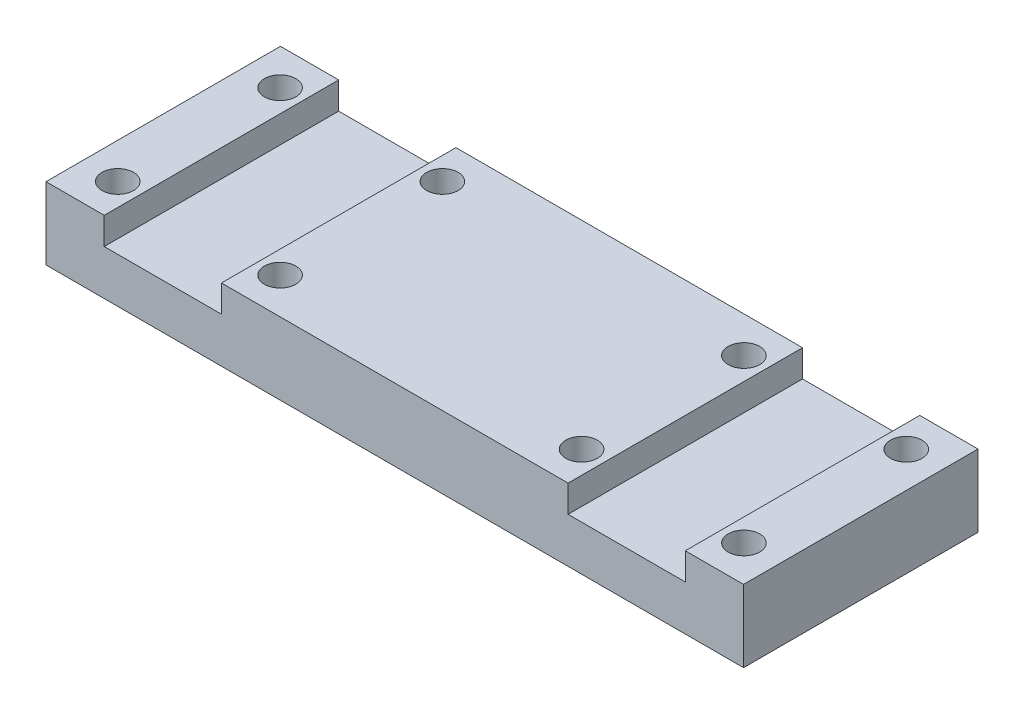
SolidWorks part; units mm, degrees
ref_plane "Front Plane" through (0, 0, 0) normal (0, 0, 1) x (1, 0, 0)
ref_plane "Top Plane" through (0, 0, 0) normal (0, 1, 0) x (1, 0, 0)
ref_plane "Right Plane" through (0, 0, 0) normal (1, 0, 0) x (0, 0, -1)
sketch "Sketch1" plane through (0, 0, 0) normal (0, 1, 0) x (1, 0, 0)
  line L1 (-77.35, -26) -> (77.35, -26)
  line L2 (-77.35, -26) -> (-77.35, 26)
  line L3 (-77.35, 26) -> (77.35, 26)
  line L4 (77.35, -26) -> (77.35, 26)
  line L5 (-77.35, -26) -> (77.35, 26) construction
  line L6 (-77.35, 26) -> (77.35, -26) construction
  point P0 (0, 0)
  dimension "D1" = 52
  dimension "D2" = 154.7
extrude "Boss-Extrude1" add sketch "Sketch1" along normal blind 16
sketch "Sketch2" plane through (77.35, 0, 0) normal (1, 0, 0) x (0, 0, -1)
  line L0 (-26, 16) -> (26, 16) construction
  line L1 (-13, 16) -> (13, 16)
  line L2 (-13, 16) -> (-13, 10)
  line L3 (-13, 10) -> (13, 10)
  line L4 (13, 16) -> (13, 10)
  point P6 (0, 16)
  point P7 (0, 16)
  dimension "D1" = 26
  dimension "D2" = 6
extrude "Cut-Extrude1" [suppressed] cut sketch "Sketch2" against normal through all
sketch "Sketch3" plane through (0, 16, 0) normal (0, 1, 0) x (1, 0, 0)
  line L0 (-77.35, 26) -> (-77.35, -26) construction
  line L1 (-33.4356, -18) -> (-69.4356, -18) construction
  line L2 (-33.4356, -18) -> (-33.4356, 18) construction
  line L3 (-33.4356, 18) -> (-69.4356, 18) construction
  line L4 (-69.4356, -18) -> (-69.4356, 18) construction
  line L5 (-33.4356, -18) -> (-69.4356, 18) construction
  line L6 (-33.4356, 18) -> (-69.4356, -18) construction
  line L9 (-75.85, 18) -> (-72.6428, 12.445) construction
  line L10 (-72.6428, 12.445) -> (-66.2285, 12.445) construction
  line L11 (-66.2285, 12.445) -> (-63.0213, 18) construction
  line L12 (-63.0213, 18) -> (-66.2285, 23.555) construction
  line L13 (-66.2285, 23.555) -> (-72.6428, 23.555) construction
  line L14 (-72.6428, 23.555) -> (-75.85, 18) construction
  circle A0 centre (-69.4356, 18) radius 3.5
  circle A1 centre (-33.4356, 18) radius 3.5
  circle A2 centre (-33.4356, -18) radius 3.5
  circle A3 centre (-69.4356, -18) radius 3.5
  circle A4 centre (-69.4356, 18) radius 5.555 construction
  point P0 (-51.4356, 0)
  dimension "D1" = 36
  dimension "D2" = 7
  dimension "D3" = 11.11
  dimension "D4" = 1.5
extrude "Cut-Extrude2" cut sketch "Sketch3" against normal through all
sketch "Sketch4" plane through (0, 0, 0) normal (0, -1, 0) x (1, 0, 0)
  line L1 (-66.2285, 12.445) -> (-63.0213, 18)
  line L2 (-63.0213, 18) -> (-66.2285, 23.555)
  line L3 (-66.2285, 23.555) -> (-72.6428, 23.555)
  line L4 (-72.6428, 23.555) -> (-75.85, 18)
  line L5 (-75.85, 18) -> (-72.6428, 12.445)
  line L6 (-72.6428, 12.445) -> (-66.2285, 12.445)
  line L7 (-30.2285, 12.445) -> (-27.0213, 18)
  line L8 (-27.0213, 18) -> (-30.2285, 23.555)
  line L9 (-30.2285, 23.555) -> (-36.6428, 23.555)
  line L10 (-36.6428, 23.555) -> (-39.85, 18)
  line L11 (-39.85, 18) -> (-36.6428, 12.445)
  line L12 (-36.6428, 12.445) -> (-30.2285, 12.445)
  line L13 (-36.6428, -12.445) -> (-39.85, -18)
  line L14 (-39.85, -18) -> (-36.6428, -23.555)
  line L15 (-36.6428, -23.555) -> (-30.2285, -23.555)
  line L16 (-30.2285, -23.555) -> (-27.0213, -18)
  line L17 (-27.0213, -18) -> (-30.2285, -12.445)
  line L18 (-30.2285, -12.445) -> (-36.6428, -12.445)
  line L19 (-66.2285, -12.445) -> (-72.6428, -12.445)
  line L20 (-72.6428, -12.445) -> (-75.85, -18)
  line L21 (-75.85, -18) -> (-72.6428, -23.555)
  line L22 (-72.6428, -23.555) -> (-66.2285, -23.555)
  line L23 (-66.2285, -23.555) -> (-63.0213, -18)
  line L24 (-63.0213, -18) -> (-66.2285, -12.445)
  circle A0 centre (-69.4356, 18) radius 5.555 construction
  circle A1 centre (-33.4356, 18) radius 5.555 construction
  circle A2 centre (-33.4356, -18) radius 5.555 construction
  circle A3 centre (-69.4356, -18) radius 5.555 construction
  dimension "D1" = 11.11
extrude "Cut-Extrude3" [suppressed] cut sketch "Sketch4" against normal blind 5.5
ref_plane "Plane1" through (0, 0, 0) normal (-1, 0, 0) x (0, 0, 1)
mirror "Mirror1" about plane through (0, 0, 0) normal (-1, 0, 0) of "Cut-Extrude3", "Cut-Extrude2"
sketch "Sketch5" plane through (0, 0, 26) normal (0, 0, 1) x (1, 0, 0)
  line L0 (-69.4356, 16) -> (-33.4356, 16) construction
  line L1 (-69.4356, 0) -> (-69.4356, 16) construction
  line L2 (-77.35, 16) -> (77.35, 16) construction
  line L3 (-33.4356, 0) -> (-33.4356, 16) construction
  line L5 (-64.4356, 16) -> (-38.4356, 16)
  line L6 (-64.4356, 16) -> (-64.4356, 10)
  line L7 (-64.4356, 10) -> (-38.4356, 10)
  line L8 (-38.4356, 16) -> (-38.4356, 10)
  point P12 (-51.4356, 16)
  point P13 (-51.4356, 16)
  dimension "D1" = 26
  dimension "D2" = 6
extrude "Cut-Extrude4" cut sketch "Sketch5" against normal through all
mirror "Mirror2" about plane through (0, 0, 0) normal (-1, 0, 0) of "Cut-Extrude4"
